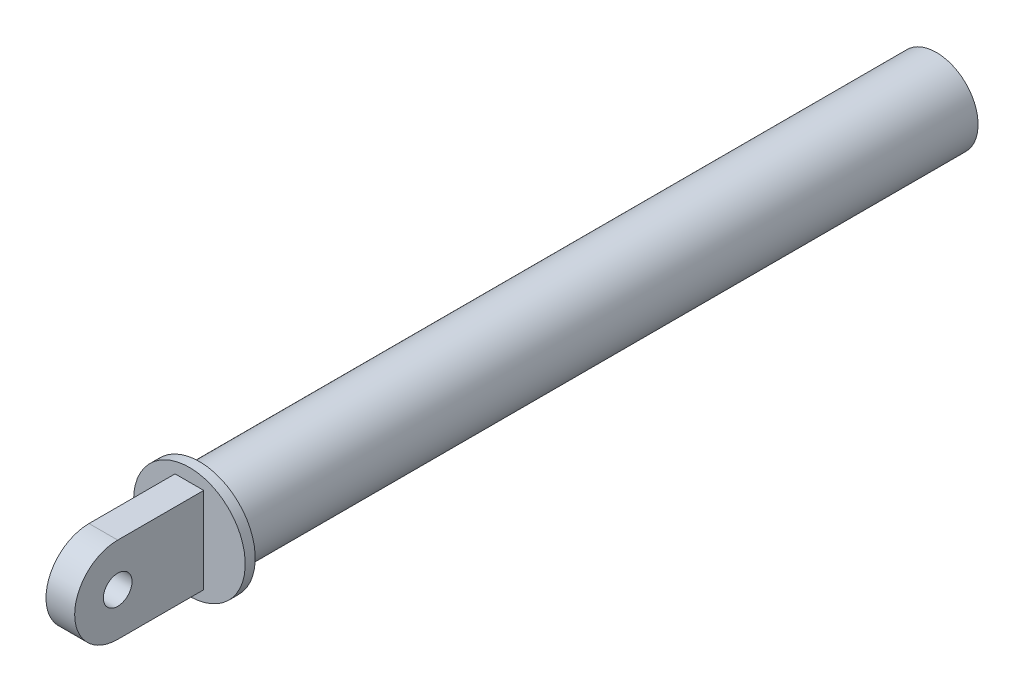
SolidWorks part; units mm, degrees
ref_plane "Front Plane" through (0, 0, 0) normal (0, 0, 1) x (1, 0, 0)
ref_plane "Top Plane" through (0, 0, 0) normal (0, 1, 0) x (1, 0, 0)
ref_plane "Right Plane" through (0, 0, 0) normal (1, 0, 0) x (0, 0, -1)
sketch "Sketch1" plane through (0, 0, 0) normal (1, 0, 0) x (0, 0, -1)
  line L1 (0, 15) -> (30, 15)
  line L2 (0, 5) -> (0, -5)
  line L3 (0, -15) -> (30, -15)
  line L4 (30, 15) -> (30, -15)
  circle A0 centre (0, 0) radius 5
  arc A1 (0, 15) -> (0, -15) centre (0, 0) ccw
  dimension "D1" = 30
  dimension "D2" = 10
  dimension "D3" = 30
extrude "Boss-Extrude1" add sketch "Sketch1" along normal mid plane 10 contours L1 A1 L3 L4 A0
sketch "Sketch2" plane through (0, 0, 0) normal (1, 0, 0) x (0, 0, -1)
  line L0 (30, 0) -> (30, 19.4639)
  line L1 (30, 15) -> (30, -15) construction
  line L2 (30, 19.4639) -> (33.5003, 19.4639)
  line L3 (33.5003, 19.4639) -> (33.5003, 14.5253)
  line L4 (33.5003, 14.5253) -> (290.4848, 14.5253)
  line L5 (290.4848, 14.5253) -> (290.4848, 0)
  line L6 (290.4848, 0) -> (30, 0)
revolve "Revolve1" add sketch "Sketch2" angle 360 about L6
